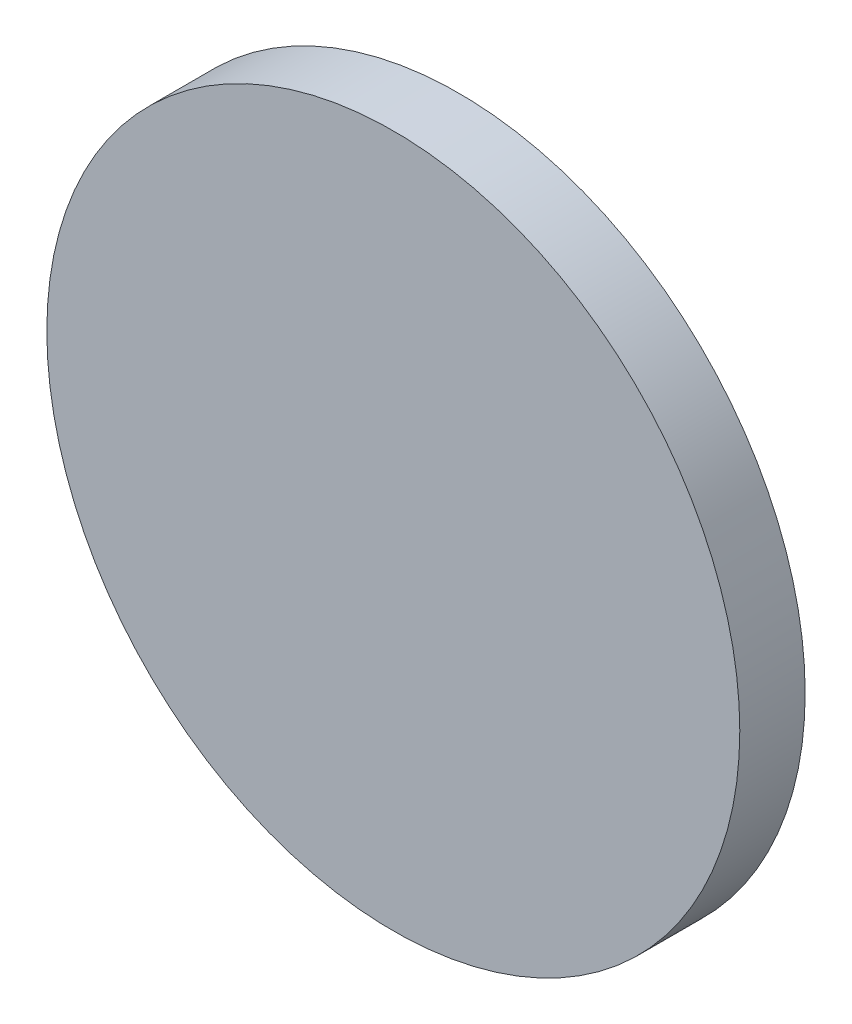
SolidWorks part; units mm, degrees
ref_plane "Front Plane" through (0, 0, 0) normal (0, 0, 1) x (1, 0, 0)
ref_plane "Top Plane" through (0, 0, 0) normal (0, 1, 0) x (1, 0, 0)
ref_plane "Right Plane" through (0, 0, 0) normal (1, 0, 0) x (0, 0, -1)
sketch "Sketch1" plane through (0, 0, 0) normal (0, 0, 1) x (1, 0, 0)
  circle A0 centre (0, 0) radius 53
extrude "Boss-Extrude1" add sketch "Sketch1" along normal blind 10
